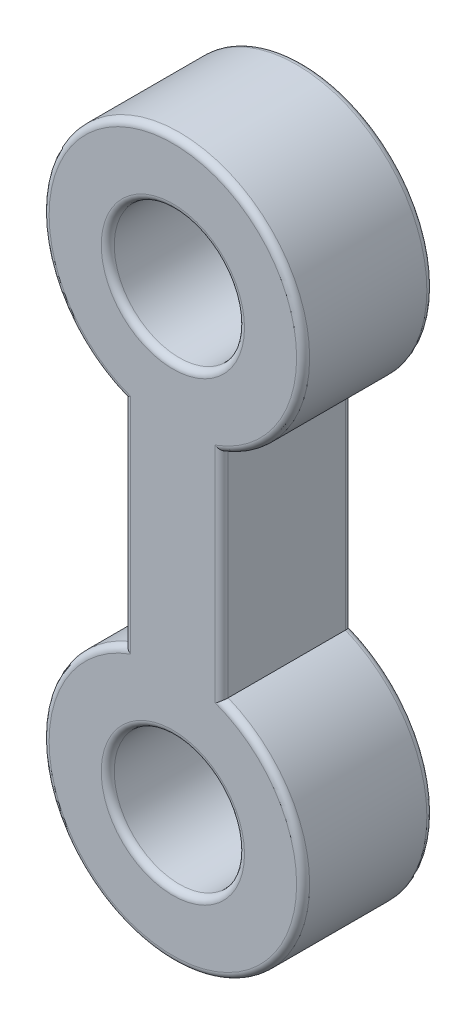
SolidWorks part; units mm, degrees
ref_plane "Front Plane" through (0, 0, 0) normal (0, 0, 1) x (1, 0, 0)
ref_plane "Top Plane" through (0, 0, 0) normal (0, 1, 0) x (1, 0, 0)
ref_plane "Right Plane" through (0, 0, 0) normal (1, 0, 0) x (0, 0, -1)
sketch "Sketch1" plane through (0, 0, 0) normal (0, 0, 1) x (1, 0, 0)
  line L0 (0, 0) -> (0, -200) construction
  line L1 (-7.5, -18.5405) -> (-7.5, -51.4595)
  line L2 (7.5, -18.5405) -> (7.5, -51.4595)
  line L3 (0, -60) -> (0, -70) construction
  circle A0 centre (0, 0) radius 10
  arc A1 (7.5, -18.5405) -> (-7.5, -18.5405) centre (0, 0) ccw
  circle A2 centre (0, -70) radius 10
  arc A3 (-7.5, -51.4595) -> (7.5, -51.4595) centre (0, -70) ccw
  dimension "D1" = 40
  dimension "D2" = 20
  dimension "D3" = 70
  dimension "D4" = 15
extrude "Boss-Extrude1" add sketch "Sketch1" along normal mid plane 20
fillet "Fillet1" radius 1 12 edges at (10, -70, -10) (10, 0, -10) (-7.5, -35, -10) (0, -90, -10) (7.5, -35, -10) (0, 20, -10) (10, -70, 10) (7.5, -35, 10) (0, -90, 10) (-7.5, -35, 10) (0, 20, 10) (10, 0, 10)
